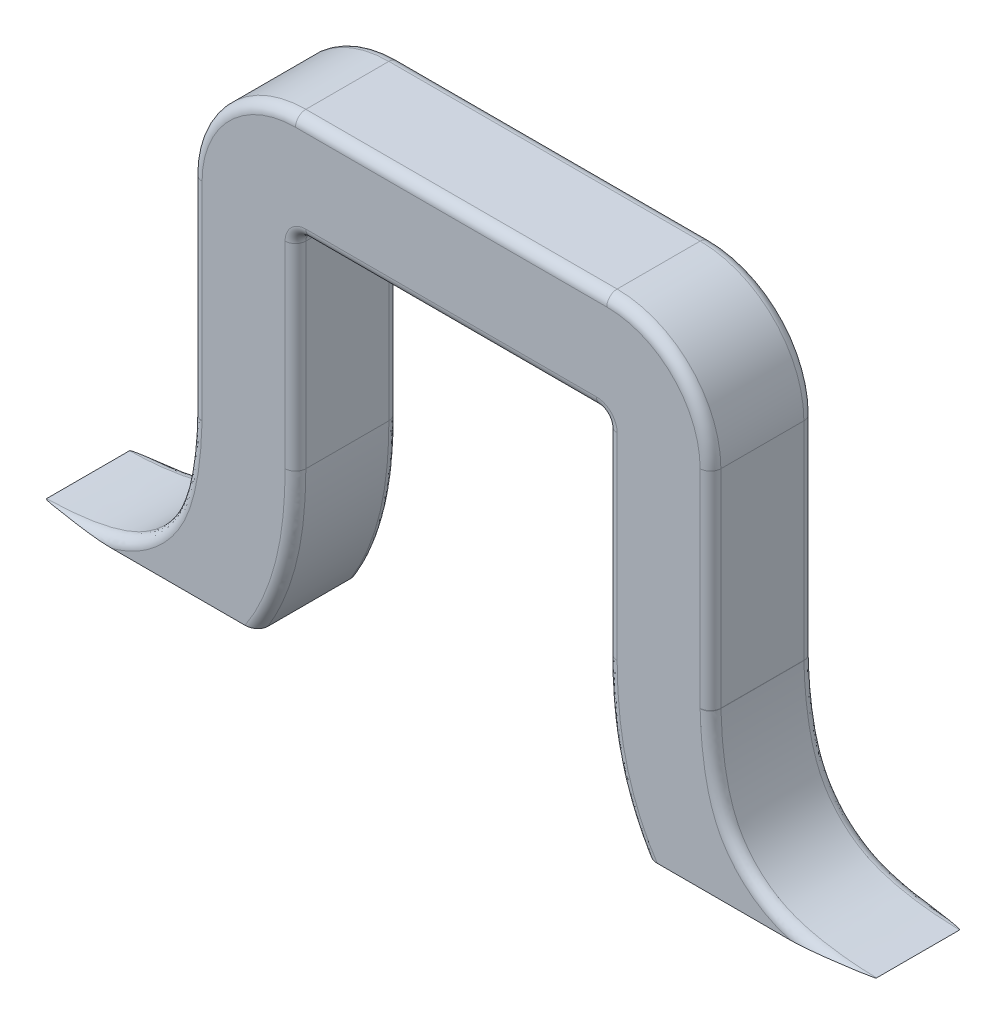
SolidWorks part; units mm, degrees
ref_plane "Front Plane" through (0, 0, 0) normal (0, 0, 1) x (1, 0, 0)
ref_plane "Top Plane" through (0, 0, 0) normal (0, 1, 0) x (1, 0, 0)
ref_plane "Right Plane" through (0, 0, 0) normal (1, 0, 0) x (0, 0, -1)
sketch "Sketch1" plane through (0, 0, 0) normal (0, 0, 1) x (1, 0, 0)
  line L0 (-2, 0) -> (-2, 2.5)
  line L1 (-2, 2.5) -> (2, 2.5)
  line L2 (2, 2.5) -> (2, 0)
  line L3 (-13.7165, -2) -> (8.7952, -2) construction
  line L4 (-2, 0) -> (-2, -2) construction
  line L5 (-2, -2) -> (-4, -2) construction
  line L6 (2, 0) -> (2, -2) construction
  line L7 (2, -2) -> (4, -2) construction
  line L8 (2.5, 3) -> (2.5, 0)
  line L9 (-2.5, 3) -> (2.5, 3)
  line L10 (-2.5, 0) -> (-2.5, 3)
  line L11 (1.5, 2) -> (1.5, 0)
  line L12 (-1.5, 2) -> (1.5, 2)
  line L13 (-1.5, 0) -> (-1.5, 2)
  line L14 (4, -1.5) -> (4, -2.5)
  line L15 (-4, -1.5) -> (-4, -2.5)
  line L16 (-4, -1.5) -> (-1.8671, -1.5)
  line L17 (4, -1.5) -> (1.8671, -1.5)
  spline S0 degree 2 poles (-2, 0) (-2, -2) (-4, -2) knots 0 0 0 1 1 1
  spline S1 degree 2 poles (2, 0) (2, -2) (4, -2) knots 0 0 0 1 1 1
  spline S2 degree 1 poles (2.5, 0) (4, -1.5) knots 0 0 1 1 construction
  spline S3 degree 1 poles (-2.5, 0) (-4, -1.5) knots 0 0 1 1 construction
  spline S4 degree 2 poles (4, -1.5) (3.3476, -1.4835) (2.8339, -1.1661) (2.5165, -0.6524) (2.5, 0) knots 0 0 0 0.375 0.625 1 1 1
  spline S5 degree 2 poles (-2.5, 0) (-2.5165, -0.6524) (-2.8339, -1.1661) (-3.3476, -1.4835) (-4, -1.5) knots 0 0 0 0.375 0.625 1 1 1
  spline S6 degree 1 poles (1.5, 0) (4, -2.5) knots 0 0 1 1 construction
  spline S7 degree 1 poles (-1.5, 0) (-4, -2.5) knots 0 0 1 1 construction
  spline S8 degree 2 poles (4, -2.5) (3.1515, -2.5158) (2.2224, -1.9671) (1.9217, -1.5914) (1.7977, -1.3847) (1.5767, -0.9107) (1.5, -0.2398) (1.5, 0) knots 0 0 0 0.375 0.555209 0.625 0.680209 0.893403 1 1 1
  spline S9 degree 2 poles (-1.5, 0) (-1.5, -0.2398) (-1.5767, -0.9107) (-1.7977, -1.3847) (-1.9217, -1.5914) (-2.2224, -1.9671) (-3.1515, -2.5158) (-4, -2.5) knots 0 0 0 0.106597 0.319791 0.375 0.444791 0.625 1 1 1
  point P3 (0, 2.5)
  dimension "D1" = 4
  dimension "D2" = 2.5
  dimension "D3" = 2
  dimension "D4" = 2
  dimension "D5" = 2
  dimension "D6" = 0.5
  dimension "D7" = 0.5
extrude "Boss-Extrude1" add sketch "Sketch1" along normal blind 1 contours L10 S5 L15 S0 L0 L1 L2 S1 L14 S4 L8 L9 | S9 L13 L12 L11 S8 L14 S1 L2 L1 L0 S0 L15
fillet "Fillet1" radius 1 2 edges at (2.5, 3, 0.5) (-2.5, 3, 0.5)
fillet "Fillet2" radius 0.1 28 edges at (0, 2, 1) (0, 2, 0) (1.5, 2, 0.5) (1.5, 1, 1) (1.5, 1, 0) (2.5, 0, 0.5) (2.5, 1, 1) (2.5, 1, 0) (2.2071, 2.7071, 0) (2.2071, 2.7071, 1) (-2.2071, 2.7071, 0) (-2.2071, 2.7071, 1) (-2.5, 0, 0.5) (-2.5, 1, 0) (-2.5, 1, 1) (0, 3, 0) (0, 3, 1) (-1.5, 1, 1) (-1.5, 2, 0.5) (-1.5, 1, 0)
